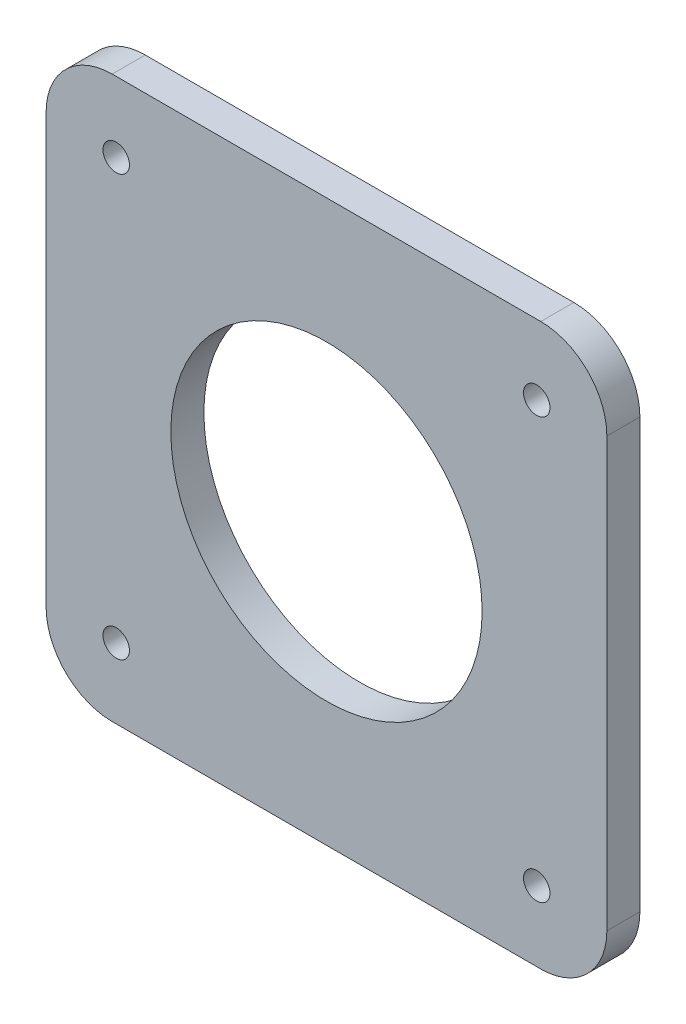
SolidWorks part; units mm, degrees
ref_plane "Front Plane" through (0, 0, 0) normal (0, 0, 1) x (1, 0, 0)
ref_plane "Top Plane" through (0, 0, 0) normal (0, 1, 0) x (1, 0, 0)
ref_plane "Right Plane" through (0, 0, 0) normal (1, 0, 0) x (0, 0, -1)
sketch "Sketch1" plane through (0, 0, 0) normal (0, 0, 1) x (1, 0, 0)
  line L1 (-5.5355, 65.4307) -> (59.3145, 65.4307)
  line L2 (-15.5355, 55.4307) -> (-15.5355, -9.4193)
  line L3 (-5.5355, -19.4193) -> (59.3145, -19.4193)
  line L4 (69.3145, 55.4307) -> (69.3145, -9.4193)
  circle A0 centre (26.8895, 23.0057) radius 23.55
  arc A1 (59.3145, 65.4307) -> (69.3145, 55.4307) centre (59.3145, 55.4307) cw
  arc A2 (59.3145, -19.4193) -> (69.3145, -9.4193) centre (59.3145, -9.4193) ccw
  arc A3 (-15.5355, -9.4193) -> (-5.5355, -19.4193) centre (-5.5355, -9.4193) ccw
  arc A4 (-5.5355, 65.4307) -> (-15.5355, 55.4307) centre (-5.5355, 55.4307) ccw
  circle A5 centre (-4.9255, 54.8207) radius 2
  circle A6 centre (-4.9255, -8.8093) radius 2
  circle A7 centre (58.7045, 54.8207) radius 2
  circle A8 centre (58.7045, -8.8093) radius 2
  dimension "D1" = 10
  dimension "D2" = 10
  dimension "D3" = 10
  dimension "D4" = 10
  dimension "D5" = 47.1
  dimension "D6" = 84.85
extrude "Boss-Extrude1" add sketch "Sketch1" along normal blind 5
